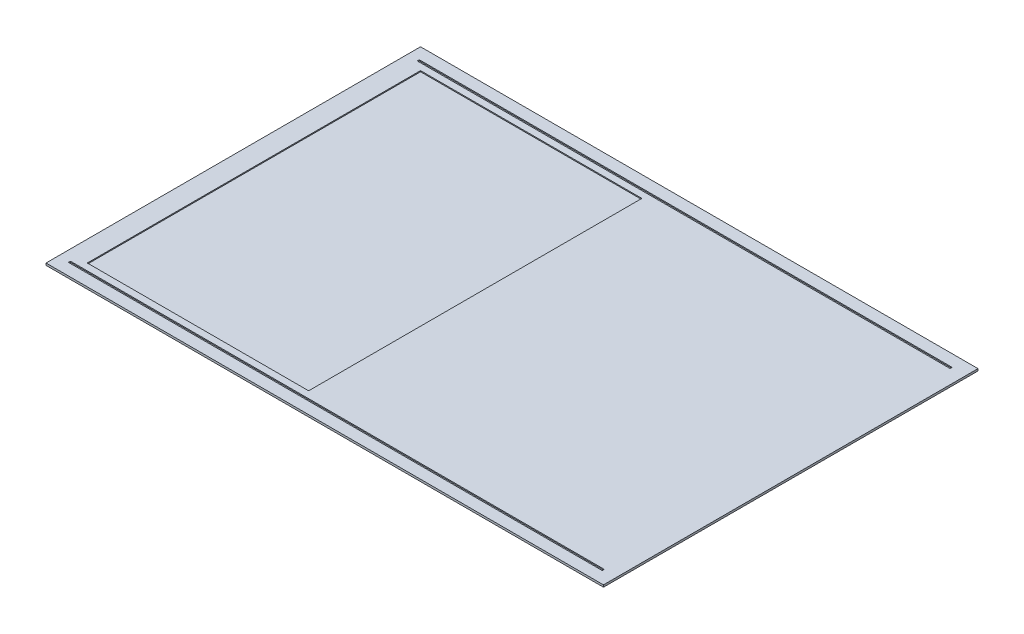
SolidWorks part; units mm, degrees
ref_plane "Front Plane" through (0, 0, 0) normal (0, 0, 1) x (1, 0, 0)
ref_plane "Top Plane" through (0, 0, 0) normal (0, 1, 0) x (1, 0, 0)
ref_plane "Right Plane" through (0, 0, 0) normal (1, 0, 0) x (0, 0, -1)
sketch "Sketch1" plane through (0, 0, 0) normal (0, 1, 0) x (1, 0, 0)
  line L0 (-459.6764, -794.6526) -> (-459.6764, -4022.6526)
  line L1 (-2603.7764, -794.6526) -> (-459.6764, -794.6526)
  line L2 (-2603.7764, -794.6526) -> (-2603.7764, -4022.6526)
  line L3 (-2603.7764, -4022.6526) -> (-459.6764, -4022.6526)
  line L6 (3503.0272, -594.6526) -> (-2803.7764, -594.6526)
  line L7 (-2803.7764, -594.6526) -> (-2803.7764, -4222.6526)
  line L8 (-2803.7764, -4222.6526) -> (2596.2236, -4222.6526)
  line L9 (2596.2236, -4222.6526) -> (2596.2236, -594.6526)
  line L10 (2596.2236, -594.6526) -> (3503.0272, -594.6526)
  dimension "D1" = 3228
  dimension "D3" = 2144.1
  dimension "D4" = 200
  dimension "D5" = 200
  dimension "D6" = 200
extrude "Boss-Extrude1" add sketch "Sketch1" along normal blind 20 contours L8 L9 L6 L7 L3 L2 L1 L0
sketch "Sketch4" plane through (0, 0, 0) normal (0, 1, 0) x (1, 0, 0)
  line L1 (-2603.7764, -794.6526) -> (-459.6764, -794.6526)
  line L2 (-2603.7764, -794.6526) -> (-2603.7764, -4022.6526)
  line L3 (-2603.7764, -4022.6526) -> (-459.6764, -4022.6526)
  line L4 (-459.6764, -794.6526) -> (-459.6764, -4022.6526)
extrude "Boss-Extrude2" add sketch "Sketch4" along normal blind 10
sketch "Sketch5" plane through (0, 20, 0) normal (0, 1, 0) x (1, 0, 0)
  line L2 (-2700.1323, -718.6526) -> (-2700.1323, -729.2457)
  line L4 (2470.6648, -4088.6526) -> (2470.6648, -4098.6526)
  line L6 (-2700.1323, -4098.6526) -> (-2700.1323, -4108.6526)
  line L7 (-2700.1323, -4088.6526) -> (-2700.1323, -4098.6526)
  line L8 (-2700.1323, -709.2457) -> (-2700.1323, -718.6526)
  line L9 (-2700.1323, -729.2457) -> (2460.6181, -729.2457)
  line L10 (-4458.5861, -728.6526) -> (-4458.5861, -708.6526)
  line L11 (-2700.1323, -709.2457) -> (2460.6181, -709.2457)
  line L12 (2460.6181, -729.2457) -> (2460.6181, -709.2457)
  line L16 (-2700.1323, -4088.6526) -> (2470.6648, -4088.6526)
  line L17 (-7870.9293, -4088.6526) -> (-7870.9293, -4108.6526)
  line L18 (-2700.1323, -4108.6526) -> (2470.6648, -4108.6526)
  line L19 (2470.6648, -4088.6526) -> (2470.6648, -4108.6526)
  dimension "D2" = 20
  dimension "D3" = 20
extrude "Cut-Extrude1" cut sketch "Sketch5" against normal blind 10 contours L9 L12 L11 L8 L2 | L19 L18 L6 L7 L16
